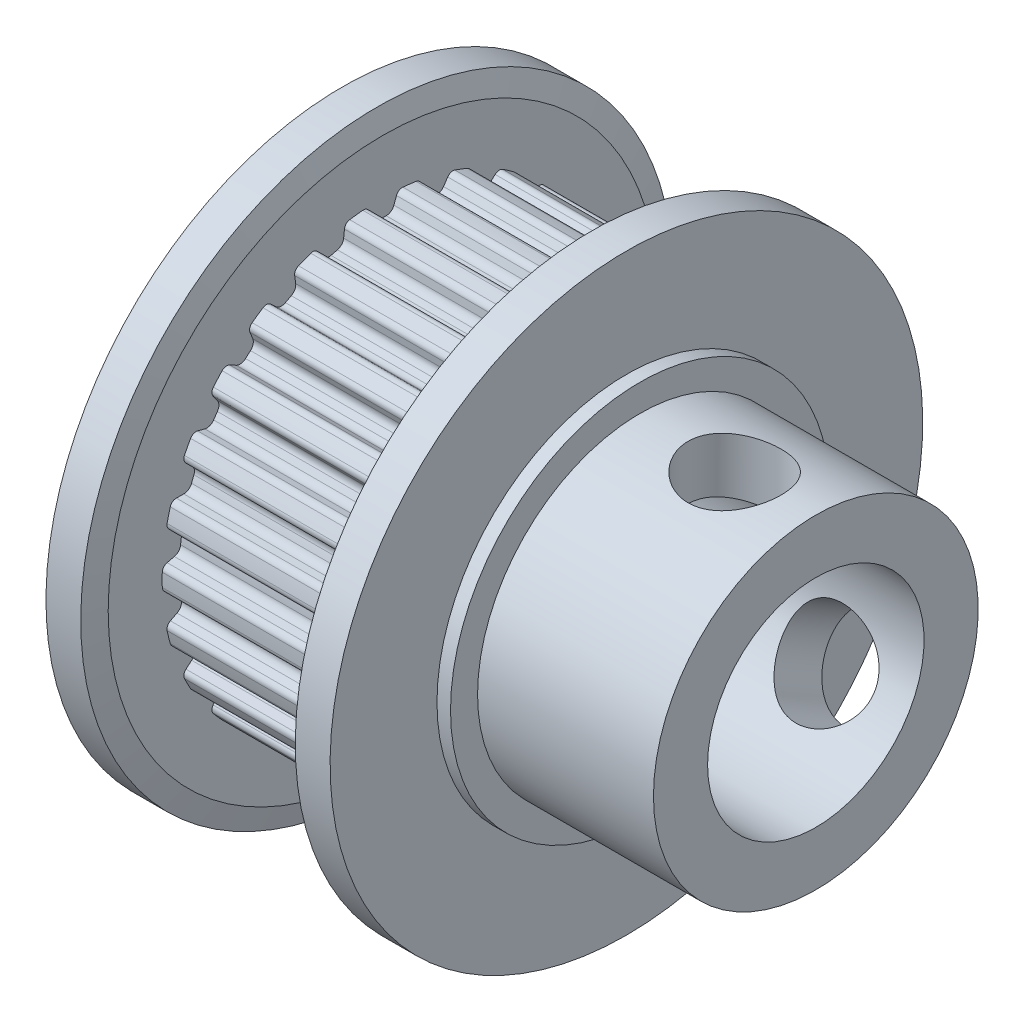
SolidWorks part; units mm, degrees
ref_plane "前视基准面" through (0, 0, 0) normal (0, 0, 1) x (1, 0, 0)
ref_plane "上视基准面" through (0, 0, 0) normal (0, 1, 0) x (1, 0, 0)
ref_plane "右视基准面" through (0, 0, 0) normal (1, 0, 0) x (0, 0, -1)
sketch "草图1" plane through (0, 0, 0) normal (0, 0, 1) x (1, 0, 0)
  line L0 (-5.75, 7) -> (-3.75, 7)
  line L1 (-3.75, 7) -> (-3.75, 8.155)
  line L2 (-3.75, 8.155) -> (3.75, 8.155)
  line L3 (0, 0) -> (0, 8.155) construction
  line L4 (-5.75, 7) -> (-5.75, 0)
  line L5 (5.75, 7) -> (5.75, 0)
  line L6 (3.75, 7) -> (3.75, 8.155)
  line L7 (5.75, 7) -> (3.75, 7)
  line L8 (-5.75, 0) -> (5.75, 0)
  dimension "D1" = 7
  dimension "D2" = 8.155
  dimension "D3" = 7.5
  dimension "D4" = 11.5
revolve "旋转1" add sketch "草图1" angle 360 about L8
sketch "草图3" plane through (0, 0, 0) normal (1, 0, 0) x (0, 0, -1)
  line L0 (0, 0) -> (0, 8.155) construction
  line L1 (-0.335, 7.5075) -> (-0.5636, 8.1355)
  line L2 (0.5636, 8.1355) -> (0.335, 7.5075)
  arc A0 (0.5636, 8.1355) -> (-0.5636, 8.1355) centre (0, 0) ccw
  circle A1 centre (0, 0) radius 8.155 construction
  arc A2 (0.335, 7.5075) -> (-0.335, 7.5075) centre (0, 0) ccw
  dimension "D4" = 0.64
  dimension "D1" = 0.67
  dimension "D2" = 20
  dimension "D3" = 20
extrude "切除-拉伸3" cut sketch "草图3" against normal mid plane 7.5
fillet "圆角3" radius 0.23 2 edges at (0, 8.1355, -0.5636) (0, 8.1355, 0.5636)
fillet "圆角4" radius 0.3 2 edges at (0, 7.5075, -0.335) (0, 7.5075, 0.335)
pattern_circular "阵列(圆周)2" count 26 over 360 about axis through (0, 0, 0) along (1, 0, 0) of "圆角3", "切除-拉伸3", "圆角4"
sketch "草图4" plane through (0, 0, 0) normal (0, 0, 1) x (1, 0, 0)
  line L0 (-5.25, 10.95) -> (-5.25, 7)
  line L1 (-3.75, 7) -> (-5.75, 7) construction
  line L2 (5.25, 10.95) -> (5.25, 7)
  line L3 (-5.25, 10.95) -> (-3.9644, 10.95)
  line L4 (-3.9644, 10.95) -> (-3.75, 10.15)
  line L5 (-3.75, 10.15) -> (-3.75, 7)
  line L6 (-3.75, 7) -> (-5.25, 7)
  line L7 (-3.75, 8.155) -> (-3.75, -8.155) construction
  line L9 (0, 0) -> (0, 9.52) construction
  line L11 (-5.75, 0) -> (5.75, 0) construction
  line L12 (-5.75, 7) -> (-5.75, -7) construction
  line L13 (5.75, -7) -> (5.75, 7) construction
  line L14 (3.75, 10.15) -> (3.75, 7)
  line L15 (3.75, 7) -> (5.25, 7)
  line L17 (3.9644, 10.95) -> (3.75, 10.15)
  line L18 (5.25, 10.95) -> (3.9644, 10.95)
  dimension "D1" = 1.5
  dimension "D2" = 15
  dimension "D3" = 10.95
  dimension "D4" = 0.8
revolve "旋转2" add sketch "草图4" angle 360 about L11
sketch "草图5" plane through (0, 0, 0) normal (0, 0, 1) x (1, 0, 0)
  line L0 (5.75, -7) -> (5.75, 7) construction
  line L1 (5.75, 0) -> (12.25, 0)
  line L2 (5.75, 0) -> (5.75, 6)
  line L3 (5.75, 6) -> (12.25, 6)
  line L4 (12.25, 0) -> (12.25, 6)
  dimension "D1" = 6
  dimension "D2" = 6.5
revolve "旋转3" add sketch "草图5" angle 360 about L1
sketch "草图37" [suppressed] plane through (0, 0, 0) normal (0, 0, 1) x (1, 0, 0)
  line L0 (-5, 0) -> (5, 0) construction
  line L1 (-5, 8.95) -> (-3, 8.95)
  line L2 (-5, 8.95) -> (-5, 5.5)
  line L3 (-5, 5.5) -> (-3, 5.5)
  line L4 (-3, 8.95) -> (-3, 5.5)
  line L5 (-5, 5.5) -> (-5, -5.5) construction
  line L6 (5, -5.5) -> (5, 5.5) construction
  line L7 (0, 0) -> (0, 7.8967) construction
  line L8 (3, 8.95) -> (3, 5.5)
  line L9 (5, 5.5) -> (3, 5.5)
  line L10 (5, 8.95) -> (3, 8.95)
  line L11 (5, 8.95) -> (5, 5.5)
  dimension "D1" = 3.75
  dimension "D2" = 7
  dimension "D3" = 10.95
  dimension "D4" = 2
revolve "切除-旋转5" [suppressed] cut sketch "草图37" angle 360 about L0
sketch "草图6" [suppressed] plane through (0, 0, 0) normal (0, 0, 1) x (1, 0, 0)
  line L0 (-4.5, 5.95) -> (-4.5, 3)
  line L1 (-3, 3) -> (-5, 3) construction
  line L3 (-4.5, 5.95) -> (-3.2144, 5.95)
  line L4 (-3.2144, 5.95) -> (-3, 5.15)
  line L5 (-3, 5.15) -> (-3, 3)
  line L6 (-3, 3) -> (-4.5, 3)
  line L8 (3, 0) -> (3, 5.15)
  line L9 (3, 5.15) -> (3.2278, 6)
  line L10 (3.2278, 6) -> (11.5, 6)
  line L11 (11.5, 6) -> (11.5, 0)
  line L12 (11.5, 0) -> (3, 0)
  line L14 (-5, 0) -> (5, 0) construction
  line L15 (-5, 3) -> (-5, -3) construction
  line L16 (5, -3) -> (5, 3) construction
  dimension "D1" = 1.5
  dimension "D2" = 15
  dimension "D3" = 0.8
  dimension "D4" = 10.95
  dimension "D5" = 6
  dimension "D6" = 15
  dimension "D7" = 18
  dimension "D8" = 3.75
revolve "旋转4" [suppressed] add sketch "草图6" angle 360 about L14
sketch "草图7" plane through (-5.75, 0, 0) normal (-1, 0, 0) x (0, 0, 1)
  circle A0 centre (0, 0) radius 4
  dimension "D1" = 8
extrude "切除-拉伸4" cut sketch "草图7" against normal through all
sketch "草图31" plane through (0, 0, 0) normal (0, 1, 0) x (1, 0, 0)
  circle A0 centre (9.25, 0) radius 1.72
  dimension "D2" = 3.44
  dimension "D1" = 9.25
extrude "切除-拉伸21" cut sketch "草图31" along normal through all
cosmetic thread "装饰螺纹线9" parameters "D2"=4
sketch "草图32" plane through (0, 0, 0) normal (0, 1, 0) x (1, 0, 0)
  line L0 (0, 0) -> (-5.75, 0) construction
  line L1 (-5.75, 7) -> (-5.75, -7) construction
ref_plane "基准面5" through (0, 0, 0) normal (0, -0.5, -0.866) x (1, 0, 0)
sketch "草图33" plane through (0, 0, 0) normal (0, -0.5, -0.866) x (1, 0, 0)
  circle A0 centre (9.25, 0) radius 1.72
  dimension "D2" = 3.44
  dimension "D1" = 9.25
extrude "切除-拉伸22" cut sketch "草图33" along normal through all
cosmetic thread "装饰螺纹线10" parameters "D2"=4
sketch "草图16" [suppressed] plane through (-5, 0, 0) normal (-1, 0, 0) x (0, 0, 1)
  line L0 (-1.5, 0) -> (-1.5, 2.9)
  line L1 (-1.5, 2.9) -> (1.5, 2.9)
  line L2 (1.5, 2.9) -> (1.5, 0)
  arc A0 (-1.5, 0) -> (1.5, 0) centre (0, 0) ccw
  dimension "D2" = 4
  dimension "D1" = 3
  dimension "D3" = 5.4
extrude "切除-拉伸10" [suppressed] cut sketch "草图16" against normal through all
sketch "草图27" [suppressed] plane through (11.5, 0, 0) normal (1, 0, 0) x (0, 0, -1)
  circle A0 centre (0, 0) radius 5
  dimension "D1" = 10
extrude "切除-拉伸19" [suppressed] cut sketch "草图27" against normal blind 5
sketch "草图29" [suppressed] plane through (0, 0, 0) normal (0, 0, 1) x (1, 0, 0)
  line L0 (-5, 4.5) -> (-2, 4.5)
  line L1 (-5, 5.5) -> (-5, -5.5) construction
  line L2 (-2, 4.5) -> (-2, 1.5)
  line L3 (-2, 1.5) -> (2, 1.5)
  line L4 (2, 1.5) -> (2, 5)
  line L5 (2, 5) -> (5, 5)
  line L6 (5, -5.5) -> (5, 5.5) construction
  line L7 (5, 5) -> (5, 0)
  line L8 (5, 0) -> (-5, 0)
  line L9 (-5, 0) -> (-5, 4.5)
  dimension "D1" = 4.5
  dimension "D2" = 3
  dimension "D3" = 3
  dimension "D4" = 5
  dimension "D5" = 4
revolve "切除-旋转1" [suppressed] cut sketch "草图29" angle 360 about L8
sketch "草图38" [suppressed] plane through (0, 0, 0) normal (0, 0, 1) x (1, 0, 0)
  line L0 (-5, 5.5) -> (-5, -5.5) construction
  line L1 (-5, 0) -> (0, 0)
  line L2 (-5, 0) -> (-5, 5)
  line L3 (-5, 5) -> (0, 5)
  line L4 (0, 0) -> (0, 5)
  dimension "D1" = 5
  dimension "D2" = 5
revolve "切除-旋转6" [suppressed] cut sketch "草图38" angle 360 about L1
sketch "草图36" [suppressed] plane through (0, 0, 0) normal (0, 0, 1) x (1, 0, 0)
  line L0 (0, 0) -> (-5, 0) construction
  line L1 (-3, 4.275) -> (-5, 4.275)
  line L2 (-3, 4.275) -> (-3, 5.95)
  line L3 (-3, 5.95) -> (-5, 5.95)
  line L4 (-5, 4.275) -> (-5, 5.95)
  line L5 (-5, 3) -> (-5, -3) construction
  dimension "D1" = 8.155
  dimension "D2" = 10.95
  dimension "D3" = 3.75
  dimension "D4" = 2
revolve "切除-旋转4" [suppressed] cut sketch "草图36" angle 360 about L0
sketch "草图35" [suppressed] plane through (0, 0, 0) normal (0, 0, 1) x (1, 0, 0)
  line L0 (-5, 0) -> (0, 0) construction
  line L1 (3, 4.275) -> (5, 4.275)
  line L2 (3, 4.275) -> (3, 5.95)
  line L3 (3, 5.95) -> (5, 5.95)
  line L4 (5, 4.275) -> (5, 5.95)
  line L5 (-5, 3) -> (-5, -3) construction
  dimension "D1" = 8.155
  dimension "D2" = 10.95
  dimension "D3" = 2
  dimension "D4" = 3.75
revolve "切除-旋转3" [suppressed] cut sketch "草图35" angle 360 about L0
sketch "草图39" [suppressed] plane through (0, 0, 0) normal (0, 0, 1) x (1, 0, 0)
  line L0 (-1000, 0) -> (49000, 0) construction
  line L1 (4.5, -8.95) -> (4.5, 8.95) construction
  line L2 (-4.5, 8.95) -> (4.5, 8.95)
  line L3 (-4.5, 8.95) -> (-4.5, 8)
  line L4 (-4.5, 8) -> (4.5, 8)
  line L5 (4.5, 8.95) -> (4.5, 8)
  dimension "D1" = 8
revolve "切除-旋转7" [suppressed] cut sketch "草图39" angle 360 about L0
sketch "草图40" [suppressed] plane through (0, 0, 0) normal (0, 0, 1) x (1, 0, 0)
  line L0 (11.5, 4.29) -> (5.5, 4.29)
  line L1 (11.5, -4.5) -> (11.5, 4.5) construction
  line L2 (5.5, 4.29) -> (4.7249, 3)
  line L3 (4.7249, 3) -> (11.5, 3)
  line L4 (11.5, 3) -> (11.5, 4.29)
  dimension "D1" = 59
  dimension "D2" = 1.29
  dimension "D3" = 6
  dimension "D4" = 3
revolve "切除-旋转8" [suppressed] cut sketch "草图40" angle 360 about L3
cosmetic thread "装饰螺纹线11" [suppressed] parameters "D2"=3
pattern_circular "阵列(圆周)3" [suppressed] count 4 over 360
sketch "草图41" [suppressed] plane through (0, 0, 0) normal (0, 0, 1) x (1, 0, 0)
  line L0 (11.5, 4.29) -> (5.5, 4.29)
  line L1 (11.5, -4.5) -> (11.5, 4.5) construction
  line L2 (5.5, 4.29) -> (4.7249, 3)
  line L3 (4.7249, 3) -> (11.5, 3)
  line L4 (11.5, 3) -> (11.5, 4.29)
  dimension "D1" = 59
  dimension "D2" = 3
  dimension "D3" = 1.29
  dimension "D4" = 6
revolve "切除-旋转9" [suppressed] cut sketch "草图41" angle 360 about L3
cosmetic thread "装饰螺纹线12" [suppressed] parameters "D2"=3
pattern_circular "阵列(圆周)4" [suppressed] count 3 over 360
sketch "草图42" [suppressed] plane through (0, 0, 0) normal (0, 0, 1) x (1, 0, 0)
  line L0 (11.5, 4.29) -> (5.5, 4.29)
  line L1 (11.5, -4.5) -> (11.5, 4.5) construction
  line L2 (5.5, 4.29) -> (4.7249, 3)
  line L3 (4.7249, 3) -> (11.5, 3)
  line L4 (11.5, 3) -> (11.5, 4.29)
  dimension "D1" = 59
  dimension "D2" = 3
  dimension "D3" = 1.29
  dimension "D4" = 6
revolve "切除-旋转10" [suppressed] cut sketch "草图42" angle 360 about L3
cosmetic thread "装饰螺纹线13" [suppressed] parameters "D2"=3
pattern_circular "阵列(圆周)5" [suppressed] count 6 over 360
sketch "草图43" [suppressed] plane through (0, 0, 0) normal (0, 0, 1) x (1, 0, 0)
  line L0 (11.5, -4.55) -> (11.5, 4.55) construction
  line L1 (11.5, 3) -> (-5, 3)
  line L2 (11.5, 3) -> (11.5, 4.5)
  line L3 (11.5, 4.5) -> (-5, 4.5)
  line L4 (-5, 3) -> (-5, 4.5)
  line L5 (-5, 5.5) -> (-5, -5.5) construction
  dimension "D1" = 3
  dimension "D2" = 1.5
revolve "切除-旋转12" [suppressed] cut sketch "草图43" angle 360 about L1
pattern_circular "阵列(圆周)6" [suppressed] count 4 over 360
sketch "草图44" [suppressed] plane through (0, 0, 0) normal (0, 0, 1) x (1, 0, 0)
  line L0 (11.5, -4.55) -> (11.5, 4.55) construction
  line L1 (11.5, 3) -> (-5, 3)
  line L2 (11.5, 3) -> (11.5, 4.5)
  line L3 (11.5, 4.5) -> (-5, 4.5)
  line L4 (-5, 3) -> (-5, 4.5)
  line L5 (-5, 5.5) -> (-5, -5.5) construction
  dimension "D1" = 3
  dimension "D2" = 1.5
revolve "切除-旋转13" [suppressed] cut sketch "草图44" angle 360 about L1
pattern_circular "阵列(圆周)7" [suppressed] count 3 over 360
sketch "草图45" [suppressed] plane through (0, 0, 0) normal (0, 0, 1) x (1, 0, 0)
  line L0 (11.5, -4.55) -> (11.5, 4.55) construction
  line L1 (11.5, 3) -> (-5, 3)
  line L2 (11.5, 3) -> (11.5, 4.45)
  line L3 (11.5, 4.45) -> (-5, 4.45)
  line L4 (-5, 3) -> (-5, 4.45)
  line L5 (-5, 5.5) -> (-5, -5.5) construction
  dimension "D1" = 3
  dimension "D2" = 1.45
revolve "切除-旋转14" [suppressed] cut sketch "草图45" angle 360 about L1
pattern_circular "阵列(圆周)12" [suppressed] count 6 over 360
sketch "草图46" [suppressed] plane through (0, 0, 0) normal (0, 0, 1) x (1, 0, 0)
  line L0 (-5, 4.65) -> (8, 4.65)
  line L1 (-5, 5.5) -> (-5, -5.5) construction
  line L2 (8, 4.65) -> (8, 6.25)
  line L3 (8, 6.25) -> (11.5, 6.25)
  line L4 (11.5, -4.55) -> (11.5, 4.55) construction
  line L5 (11.5, 6.25) -> (11.5, 3)
  line L6 (11.5, 3) -> (-5, 3)
  line L7 (-5, 3) -> (-5, 4.65)
  dimension "D1" = 3
  dimension "D2" = 1.65
  dimension "D3" = 3.25
  dimension "D4" = 3.5
revolve "切除-旋转15" [suppressed] cut sketch "草图46" angle 360 about L6
pattern_circular "阵列(圆周)13" [suppressed] count 4 over 360
sketch "草图47" [suppressed] plane through (0, 0, 0) normal (0, 0, 1) x (1, 0, 0)
  line L0 (-5, 4.65) -> (8, 4.65)
  line L1 (-5, 5.5) -> (-5, -5.5) construction
  line L2 (8, 4.65) -> (8, 6.25)
  line L3 (8, 6.25) -> (11.5, 6.25)
  line L4 (11.5, -4.55) -> (11.5, 4.55) construction
  line L5 (11.5, 6.25) -> (11.5, 3)
  line L6 (11.5, 3) -> (-5, 3)
  line L7 (-5, 3) -> (-5, 4.65)
  dimension "D1" = 3
  dimension "D2" = 1.65
  dimension "D3" = 3.25
  dimension "D4" = 3.5
revolve "切除-旋转16" [suppressed] cut sketch "草图47" angle 360 about L6
pattern_circular "阵列(圆周)14" [suppressed] count 3 over 360
sketch "草图48" [suppressed] plane through (0, 0, 0) normal (0, 0, 1) x (1, 0, 0)
  line L0 (-5, 4.65) -> (8, 4.65)
  line L1 (-5, 5.5) -> (-5, -5.5) construction
  line L2 (8, 4.65) -> (8, 6.25)
  line L3 (8, 6.25) -> (11.5, 6.25)
  line L4 (11.5, -4.55) -> (11.5, 4.55) construction
  line L5 (11.5, 6.25) -> (11.5, 3)
  line L6 (11.5, 3) -> (-5, 3)
  line L7 (-5, 3) -> (-5, 4.65)
  dimension "D1" = 3
  dimension "D2" = 1.65
  dimension "D3" = 3.25
  dimension "D4" = 3.5
revolve "切除-旋转17" [suppressed] cut sketch "草图48" angle 360 about L6
pattern_circular "阵列(圆周)15" [suppressed] count 6 over 360
